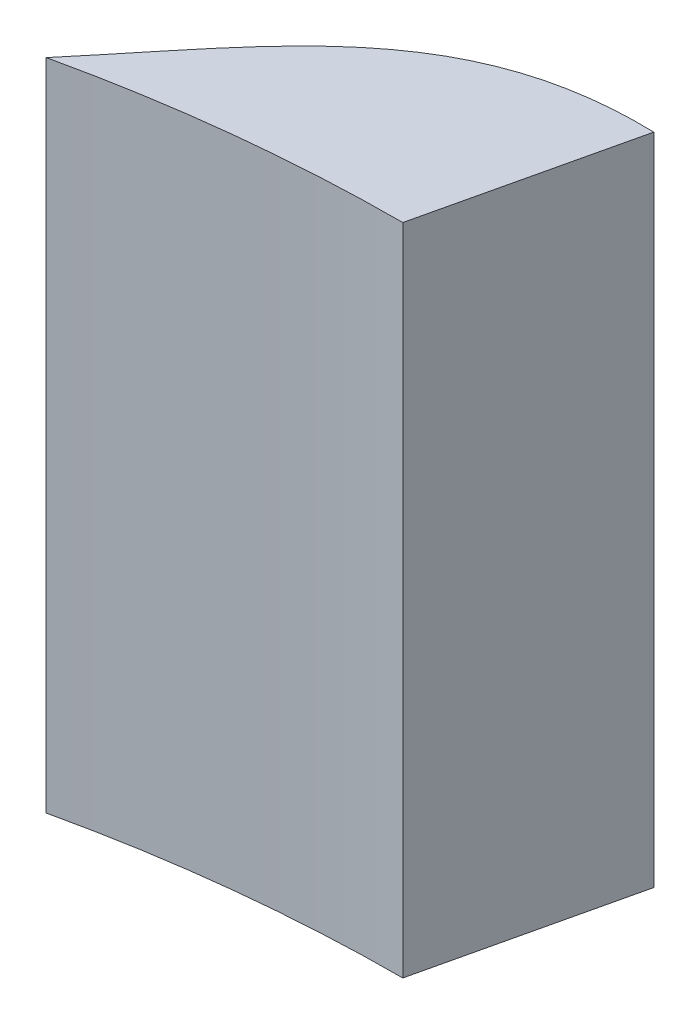
SolidWorks part; units mm, degrees
ref_plane "Front Plane" through (0, 0, 0) normal (0, 0, 1) x (1, 0, 0)
ref_plane "Top Plane" through (0, 0, 0) normal (0, 1, 0) x (1, 0, 0)
ref_plane "Right Plane" through (0, 0, 0) normal (1, 0, 0) x (0, 0, -1)
sketch "Sketch1" plane through (0, 0, 0) normal (0, 1, 0) x (1, 0, 0)
  line L0 (0, 90) -> (2.8834, 102.4594)
  line L1 (0, 0) -> (0, 90) construction
  arc A1 (-19.633, 87.8325) -> (0, 90) centre (0, 0) cw
  circle A2 centre (0, 0) radius 102.5 construction
  spline S0 degree 3 poles (2.8834, 102.4594) (-8.9608, 102.7928) (-13.2266, 95.3919) (-19.633, 87.8325) knots 0 0 0 0 1 1 1 1
  point P2 (-14.202, 96.8999)
  point P6 (2.8834, 102.4594)
  point P7 (-11.7386, 99.4482)
  point P8 (-16.2407, 97.5795)
  point P9 (-17.1546, 88.35)
  point P11 (-11.0996, 97.5203)
  point P13 (-19.633, 87.8325)
  dimension "D1" = 90
  dimension "D2" = 205
extrude "Boss-Extrude1" add sketch "Sketch1" along normal blind 40
